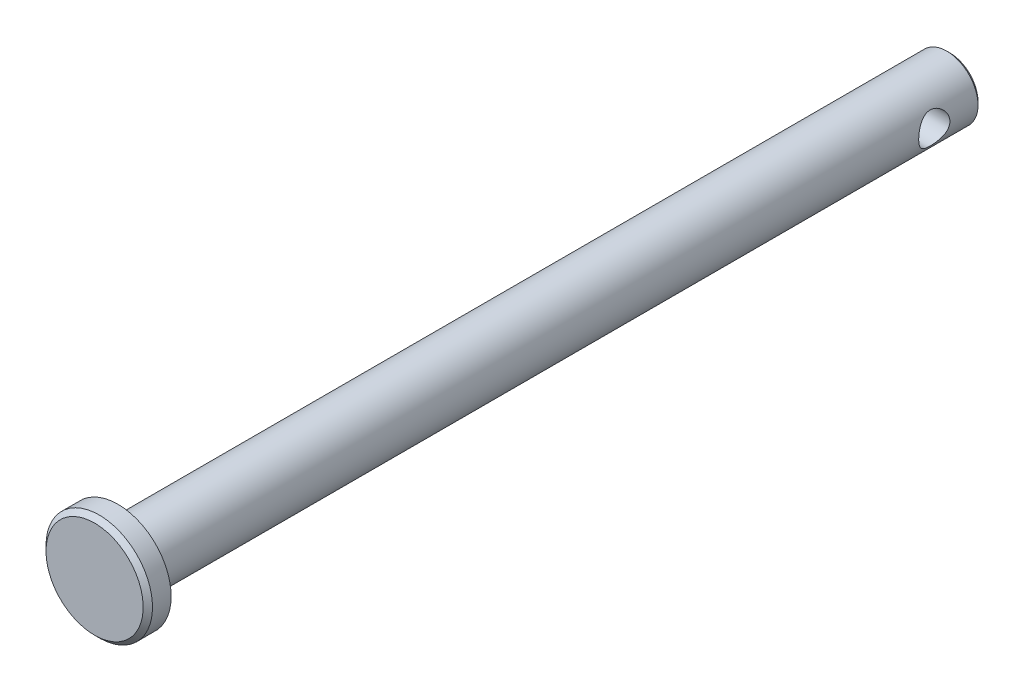
SolidWorks part; units mm, degrees
ref_plane "Front" through (0, 0, 0) normal (0, 0, 1) x (1, 0, 0)
ref_plane "Top" through (0, 0, 0) normal (0, 1, 0) x (1, 0, 0)
ref_plane "Right" through (0, 0, 0) normal (1, 0, 0) x (0, 0, -1)
sketch "Sketch1" plane through (0, 0, 0) normal (0, 0, 1) x (1, 0, 0)
  circle A0 centre (0, 0) radius 2.3813
  point P3 (0, 2.3813)
  point P4 (0, -2.3813)
  dimension "dia" = 4.7625
extrude "Extrude1" add sketch "Sketch1" along normal mid plane 63.5
sketch "Sketch2" plane through (0, 0, 31.75) normal (0, 0, 1) x (1, 0, 0)
  circle A0 centre (0, 0) radius 4.064
  dimension "head dia" = 8.128
extrude "Extrude2" add sketch "Sketch2" along normal blind 1.778
chamfer "Chamfer1" distance 0.3556 angle 45 1 edges at (4.064, 0, 33.528)
sketch "Sketch3" plane through (0, 0, 0) normal (1, 0, 0) x (0, 0, -1)
  line L0 (-31.75, -2.3813) -> (-31.75, 2.3813) construction
  circle A0 centre (28.1781, 0) radius 1.1906
  point P2 (26.9875, 0)
  dimension "hole dia" = 2.3813
  dimension "useable Lg" = 58.7375
extrude "Extrude3" cut sketch "Sketch3" against normal through all and the other way through all
chamfer "Chamfer2" distance 0.2381 angle 45 1 edges at (2.3813, 0, -31.75)
ref_plane "Plane1" through (0, 0, -28.1781) normal (0, 0, 1) x (1, 0, 0)
sketch "Sketch8" plane through (0, 0, 0) normal (1, 0, 0) x (0, 0, -1)
  line L0 (-33.528, 3.7084) -> (-33.528, -3.7084) construction
  line L1 (-33.1724, -4.064) -> (-31.75, -4.064) construction
  line L2 (31.75, -2.1431) -> (31.75, 2.1431) construction
  point P0 (-33.528, 4.064)
  point P1 (-31.75, 4.064)
  point P5 (31.75, 2.3813)
  point P8 (-33.528, -4.064)
  point P9 (31.75, -2.3813)
equation "\"D1@Chamfer1\" = \"head ht@Extrude2\" * .2"
equation "\"D1@Chamfer2\" = \"dia@Sketch1\" * .05"
